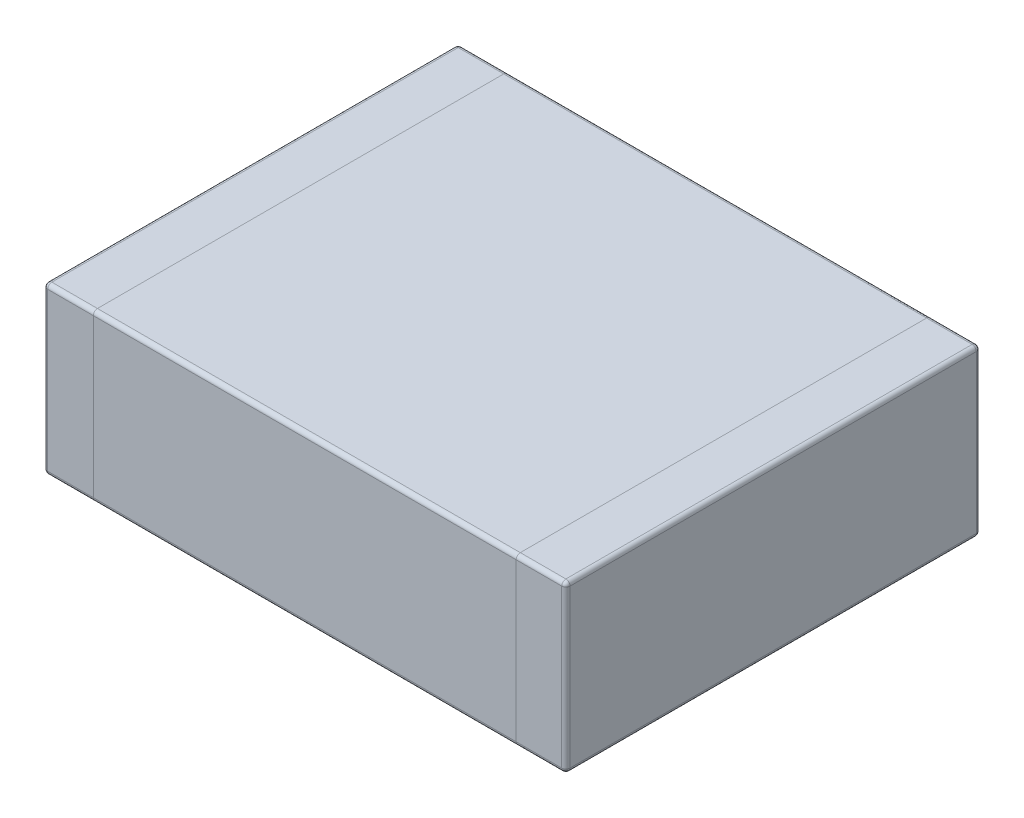
SolidWorks part; units mm, degrees
ref_plane "Front Plane" through (0, 0, 0) normal (0, 0, 1) x (1, 0, 0)
ref_plane "Top Plane" through (0, 0, 0) normal (0, 1, 0) x (1, 0, 0)
ref_plane "Right Plane" through (0, 0, 0) normal (1, 0, 0) x (0, 0, -1)
sketch "Sketch1" plane through (0, 0, 0) normal (0, 1, 0) x (1, 0, 0)
  line L1 (-3.15, -2.5) -> (3.15, -2.5)
  line L2 (-3.15, -2.5) -> (-3.15, 2.5)
  line L3 (-3.15, 2.5) -> (3.15, 2.5)
  line L4 (3.15, -2.5) -> (3.15, 2.5)
  line L5 (-3.15, -2.5) -> (3.15, 2.5) construction
  line L6 (-3.15, 2.5) -> (3.15, -2.5) construction
  point P0 (0, 0)
  dimension "D1" = 6.3
  dimension "D2" = 5
extrude "Extrude1" add sketch "Sketch1" along normal blind 2
fillet "Fillet1" radius 0.05 12 edges at (3.15, 1, -2.5) (-3.15, 1, -2.5) (-3.15, 1, 2.5) (3.15, 1, 2.5) (0, 2, 2.5) (-3.15, 2, 0) (0, 2, -2.5) (3.15, 2, 0) (0, 0, -2.5) (-3.15, 0, 0) (0, 0, 2.5) (3.15, 0, 0)
sketch "Sketch2" plane through (0, 0, 0) normal (0, 1, 0) x (1, 0, 0)
  line L0 (-3.1, 2.5) -> (3.1, 2.5) construction
  line L1 (-2.55, -2.5) -> (2.55, -2.5)
  line L2 (-2.55, -2.5) -> (-2.55, 2.5)
  line L3 (-2.55, 2.5) -> (2.55, 2.5)
  line L4 (2.55, -2.5) -> (2.55, 2.5)
  line L5 (3.1, -2.5) -> (-3.1, -2.5) construction
  line L6 (0, 2.45) -> (0, -0.6635) construction
  line L7 (3.1, 2.45) -> (-3.1, 2.45) construction
  line L9 (-3.15, -2.45) -> (-3.15, 2.45) construction
  dimension "D1" = 0.6
split line "Split Line3"
